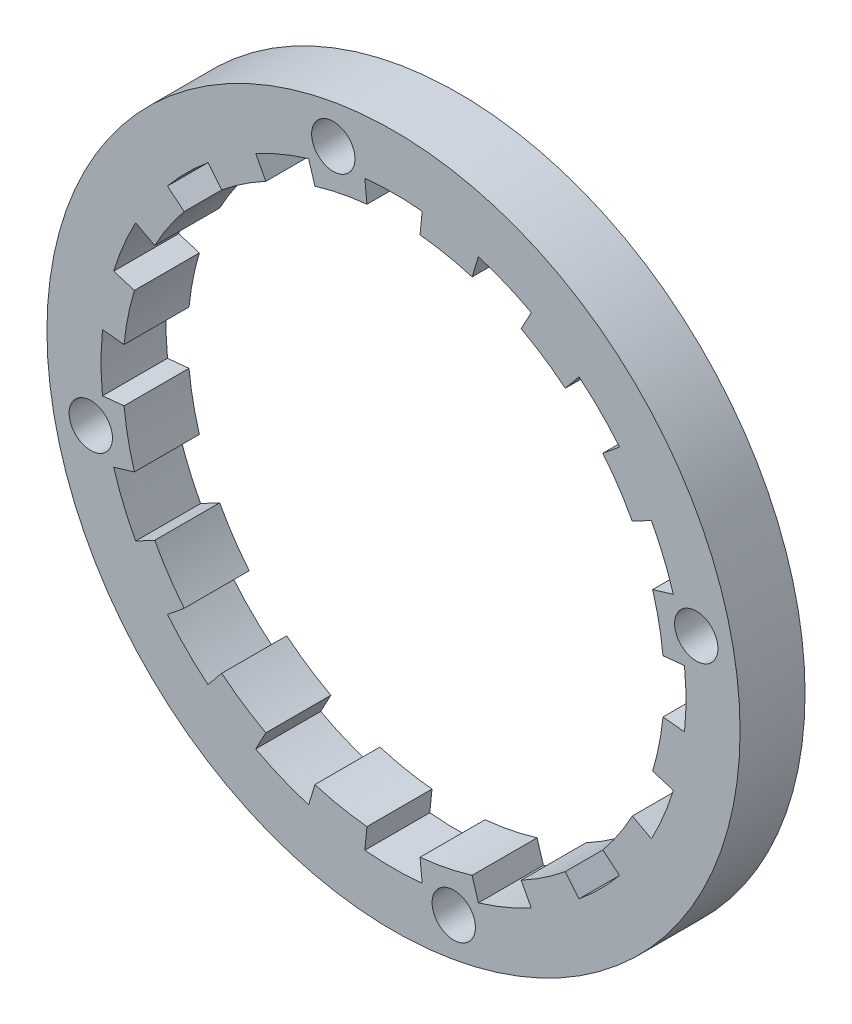
SolidWorks part; units mm, degrees
ref_plane "Plano frontal" through (0, 0, 0) normal (0, 0, 1) x (1, 0, 0)
ref_plane "Plano superior" through (0, 0, 0) normal (0, 1, 0) x (1, 0, 0)
ref_plane "Plano direito" through (0, 0, 0) normal (1, 0, 0) x (0, 0, -1)
sketch "Esboço1" plane through (0, 0, 0) normal (0, 0, 1) x (1, 0, 0)
  line L0 (0, 32) -> (0, -32) construction
  line L1 (-32, 0) -> (32, 0) construction
  line L2 (-22.6274, 22.6274) -> (22.6274, -22.6274) construction
  line L3 (22.6274, 22.6274) -> (-22.6274, -22.6274) construction
  line L4 (-29.5641, 12.2459) -> (29.5641, -12.2459) construction
  line L5 (-29.5641, -12.2459) -> (29.5641, 12.2459) construction
  line L6 (-12.2459, -29.5641) -> (12.2459, 29.5641) construction
  line L7 (12.2459, -29.5641) -> (-12.2459, 29.5641) construction
  line L40 (-5.2674, 26.4812) -> (5.2674, -26.4812) construction
  line L41 (5.2674, 26.4812) -> (-5.2674, -26.4812) construction
  line L42 (15.0004, 22.4497) -> (-15.0004, -22.4497) construction
  line L43 (22.4497, 15.0004) -> (-22.4497, -15.0004) construction
  line L44 (26.4812, 5.2674) -> (-26.4812, -5.2674) construction
  line L45 (26.4812, -5.2674) -> (-26.4812, 5.2674) construction
  line L46 (22.4497, -15.0004) -> (-22.4497, 15.0004) construction
  line L47 (15.0004, -22.4497) -> (-15.0004, 22.4497) construction
  line L48 (5.2674, -26.4812) -> (-5.2674, 26.4812) construction
  line L49 (-5.2674, -26.4812) -> (5.2674, 26.4812) construction
  line L50 (-15.0004, -22.4497) -> (15.0004, 22.4497) construction
  line L51 (-22.4497, -15.0004) -> (22.4497, 15.0004) construction
  line L52 (-26.4812, -5.2674) -> (26.4812, 5.2674) construction
  line L53 (-26.4812, 5.2674) -> (26.4812, -5.2674) construction
  line L54 (-22.4497, 15.0004) -> (22.4497, -15.0004) construction
  line L55 (-15.0004, 22.4497) -> (15.0004, -22.4497) construction
  line L56 (-7.2571, 23.9235) -> (7.2571, -23.9235) construction
  line L57 (-2.4504, 24.8796) -> (2.1564, -21.8941) construction
  line L58 (2.4504, 24.8796) -> (-2.4504, -24.8796) construction
  line L59 (7.2571, 23.9235) -> (-5.5154, -18.1819) construction
  line L60 (11.7849, 22.048) -> (-8.9565, -16.7565) construction
  line L61 (15.8598, 19.3253) -> (-12.0535, -14.6872) construction
  line L62 (14.6872, 12.0535) -> (-19.3253, -15.8598) construction
  line L63 (19.4023, 10.3707) -> (-19.4023, -10.3707) construction
  line L64 (21.0527, 6.3863) -> (-21.0527, -6.3863) construction
  line L65 (21.8941, 2.1564) -> (-21.8941, -2.1564) construction
  line L66 (21.8941, -2.1564) -> (-21.8941, 2.1564) construction
  line L67 (21.0527, -6.3863) -> (-21.0527, 6.3863) construction
  line L68 (19.4023, -10.3707) -> (-19.4023, 10.3707) construction
  line L69 (17.0062, -13.9567) -> (-17.0062, 13.9567) construction
  line L70 (13.9567, -17.0062) -> (-13.9567, 17.0062) construction
  line L71 (10.3707, -19.4023) -> (-10.3707, 19.4023) construction
  line L72 (6.3863, -21.0527) -> (-6.3863, 21.0527) construction
  line L73 (2.4504, -24.8796) -> (-2.4504, 24.8796) construction
  line L74 (-1.8623, -18.9085) -> (2.4504, 24.8796) construction
  line L75 (-6.3863, -21.0527) -> (6.3863, 21.0527) construction
  line L76 (-10.3707, -19.4023) -> (10.3707, 19.4023) construction
  line L77 (-13.9567, -17.0062) -> (13.9567, 17.0062) construction
  line L78 (-17.0062, -13.9567) -> (17.0062, 13.9567) construction
  line L79 (-19.4023, -10.3707) -> (19.4023, 10.3707) construction
  line L80 (-21.0527, -6.3863) -> (21.0527, 6.3863) construction
  line L81 (-21.8941, -2.1564) -> (21.8941, 2.1564) construction
  line L82 (-21.8941, 2.1564) -> (21.8941, -2.1564) construction
  line L83 (-21.0527, 6.3863) -> (21.0527, -6.3863) construction
  line L84 (-19.4023, 10.3707) -> (19.4023, -10.3707) construction
  line L85 (-19.3253, 15.8598) -> (14.6872, -12.0535) construction
  line L86 (-12.0535, 14.6872) -> (15.8598, -19.3253) construction
  line L87 (-8.9565, 16.7565) -> (11.7849, -22.048) construction
  line L88 (0, 0) -> (-2.6465, 26.87) construction
  line L89 (0, 0) -> (2.6465, 26.87) construction
  line L90 (-2.6465, 26.87) -> (-2.4504, 24.8796)
  line L91 (2.6465, 26.87) -> (2.4504, 24.8796)
  line L92 (7.8377, 25.8374) -> (7.2571, 23.9235)
  line L93 (12.7277, 23.8119) -> (11.7849, 22.048)
  line L94 (17.1286, 20.8713) -> (15.8598, 19.3253)
  line L95 (20.8713, 17.1286) -> (19.3253, 15.8598)
  line L96 (23.8119, 12.7277) -> (22.048, 11.7849)
  line L97 (25.8374, 7.8377) -> (23.9235, 7.2571)
  line L98 (26.87, 2.6465) -> (24.8796, 2.4504)
  line L99 (26.87, -2.6465) -> (24.8796, -2.4504)
  line L100 (25.8374, -7.8377) -> (23.9235, -7.2571)
  line L101 (23.8119, -12.7277) -> (22.048, -11.7849)
  line L102 (20.8713, -17.1286) -> (19.3253, -15.8598)
  line L103 (17.1286, -20.8713) -> (15.8598, -19.3253)
  line L104 (12.7277, -23.8119) -> (11.7849, -22.048)
  line L105 (7.8377, -25.8374) -> (7.2571, -23.9235)
  line L106 (2.6465, -26.87) -> (2.4504, -24.8796)
  line L107 (-2.6465, -26.87) -> (-2.4504, -24.8796)
  line L108 (-7.8377, -25.8374) -> (-7.2571, -23.9235)
  line L109 (-12.7277, -23.8119) -> (-11.7849, -22.048)
  line L110 (-17.1286, -20.8713) -> (-15.8598, -19.3253)
  line L111 (-20.8713, -17.1286) -> (-19.3253, -15.8598)
  line L112 (-23.8119, -12.7277) -> (-22.048, -11.7849)
  line L113 (-25.8374, -7.8377) -> (-23.9235, -7.2571)
  line L114 (-26.87, -2.6465) -> (-24.8796, -2.4504)
  line L115 (-26.87, 2.6465) -> (-24.8796, 2.4504)
  line L116 (-25.8374, 7.8377) -> (-23.9235, 7.2571)
  line L117 (-23.8119, 12.7277) -> (-22.048, 11.7849)
  line L118 (-20.8713, 17.1286) -> (-19.3253, 15.8598)
  line L119 (-17.1286, 20.8713) -> (-15.8598, 19.3253)
  line L120 (-12.7277, 23.8119) -> (-11.7849, 22.048)
  line L121 (-7.8377, 25.8374) -> (-7.2571, 23.9235)
  circle A0 centre (0, 0) radius 32
  circle A1 centre (0, 0) radius 27 construction
  arc A2 (-19.3253, 15.8598) -> (-22.048, 11.7849) centre (0, 0) ccw
  arc A3 (0, 27) -> (-2.6465, 26.87) centre (0, 0) ccw
  arc A4 (0, 27) -> (2.6465, 26.87) centre (0, 0) cw
  arc A5 (10.3325, 24.9447) -> (7.8377, 25.8374) centre (0, 0) ccw
  arc A6 (10.3325, 24.9447) -> (12.7277, 23.8119) centre (0, 0) cw
  arc A7 (19.0919, 19.0919) -> (17.1286, 20.8713) centre (0, 0) ccw
  arc A8 (19.0919, 19.0919) -> (20.8713, 17.1286) centre (0, 0) cw
  arc A9 (24.9447, 10.3325) -> (23.8119, 12.7277) centre (0, 0) ccw
  arc A10 (24.9447, 10.3325) -> (25.8374, 7.8377) centre (0, 0) cw
  arc A11 (27, 0) -> (26.87, 2.6465) centre (0, 0) ccw
  arc A12 (27, 0) -> (26.87, -2.6465) centre (0, 0) cw
  arc A13 (24.9447, -10.3325) -> (25.8374, -7.8377) centre (0, 0) ccw
  arc A14 (24.9447, -10.3325) -> (23.8119, -12.7277) centre (0, 0) cw
  arc A15 (19.0919, -19.0919) -> (20.8713, -17.1286) centre (0, 0) ccw
  arc A16 (19.0919, -19.0919) -> (17.1286, -20.8713) centre (0, 0) cw
  arc A17 (10.3325, -24.9447) -> (12.7277, -23.8119) centre (0, 0) ccw
  arc A18 (10.3325, -24.9447) -> (7.8377, -25.8374) centre (0, 0) cw
  arc A19 (0, -27) -> (2.6465, -26.87) centre (0, 0) ccw
  arc A20 (0, -27) -> (-2.6465, -26.87) centre (0, 0) cw
  arc A21 (-10.3325, -24.9447) -> (-7.8377, -25.8374) centre (0, 0) ccw
  arc A22 (-10.3325, -24.9447) -> (-12.7277, -23.8119) centre (0, 0) cw
  arc A23 (-19.0919, -19.0919) -> (-17.1286, -20.8713) centre (0, 0) ccw
  arc A24 (-19.0919, -19.0919) -> (-20.8713, -17.1286) centre (0, 0) cw
  arc A25 (-24.9447, -10.3325) -> (-23.8119, -12.7277) centre (0, 0) ccw
  arc A26 (-24.9447, -10.3325) -> (-25.8374, -7.8377) centre (0, 0) cw
  arc A27 (-27, 0) -> (-26.87, -2.6465) centre (0, 0) ccw
  arc A28 (-27, 0) -> (-26.87, 2.6465) centre (0, 0) cw
  arc A29 (-24.9447, 10.3325) -> (-25.8374, 7.8377) centre (0, 0) ccw
  arc A30 (-24.9447, 10.3325) -> (-23.8119, 12.7277) centre (0, 0) cw
  arc A31 (-19.0919, 19.0919) -> (-20.8713, 17.1286) centre (0, 0) ccw
  arc A32 (-19.0919, 19.0919) -> (-17.1286, 20.8713) centre (0, 0) cw
  arc A33 (-10.3325, 24.9447) -> (-12.7277, 23.8119) centre (0, 0) ccw
  arc A34 (-10.3325, 24.9447) -> (-7.8377, 25.8374) centre (0, 0) cw
  arc A35 (-23.9235, 7.2571) -> (-24.8796, 2.4504) centre (0, 0) ccw
  arc A36 (-24.8796, -2.4504) -> (-23.9235, -7.2571) centre (0, 0) ccw
  arc A37 (-22.048, -11.7849) -> (-19.3253, -15.8598) centre (0, 0) ccw
  arc A38 (-11.7849, 22.048) -> (-15.8598, 19.3253) centre (0, 0) ccw
  arc A39 (-2.4504, 24.8796) -> (-7.2571, 23.9235) centre (0, 0) ccw
  arc A40 (7.2571, 23.9235) -> (2.4504, 24.8796) centre (0, 0) ccw
  arc A41 (15.8598, 19.3253) -> (11.7849, 22.048) centre (0, 0) ccw
  arc A42 (22.048, 11.7849) -> (19.3253, 15.8598) centre (0, 0) ccw
  arc A43 (24.8796, 2.4504) -> (23.9235, 7.2571) centre (0, 0) ccw
  arc A44 (23.9235, -7.2571) -> (24.8796, -2.4504) centre (0, 0) ccw
  arc A45 (19.3253, -15.8598) -> (22.048, -11.7849) centre (0, 0) ccw
  arc A46 (11.7849, -22.048) -> (15.8598, -19.3253) centre (0, 0) ccw
  arc A47 (2.4504, -24.8796) -> (7.2571, -23.9235) centre (0, 0) ccw
  arc A48 (-7.2571, -23.9235) -> (-2.4504, -24.8796) centre (0, 0) ccw
  arc A49 (-15.8598, -19.3253) -> (-11.7849, -22.048) centre (0, 0) ccw
  point P55 (0, 0)
  point P72 (0, 0)
  point P121 (0, 0)
  point P202 (0, 0)
  dimension "D1" = 64
  dimension "D2" = 54
  dimension "D9" = 2
  dimension "D3" = 45
  dimension "D4" = 45
  dimension "D5" = 22.5
  dimension "D6" = 22.5
  dimension "D7" = 22.5
  dimension "D8" = 22.5
  dimension "D10" = 11.25
  dimension "D12" = 5.625
  dimension "D14" = 16
extrude "Ressalto-extrusão4" add sketch "Esboço1" along normal blind 6
sketch "Esboço2" plane through (0, 0, 6) normal (0, 0, 1) x (1, 0, 0)
  line L0 (-6.2429, 31.3851) -> (-5.5601, 27.9524)
  line L1 (-6.2429, 31.3851) -> (6.2429, -31.3851) construction
  line L2 (-5.5601, 27.9524) -> (-4.8773, 24.5196)
  line L3 (6.2429, -31.3851) -> (5.5601, -27.9524)
  line L4 (5.5601, -27.9524) -> (4.8773, -24.5196)
  circle A1 centre (0, 0) radius 32 construction
  circle A2 centre (-5.5601, 27.9524) radius 2
  arc A3 (-2.4504, 24.8796) -> (-7.2571, 23.9235) centre (0, 0) ccw construction
  circle A4 centre (5.5601, -27.9524) radius 2
  arc A5 (2.4504, -24.8796) -> (7.2571, -23.9235) centre (0, 0) ccw construction
  circle A6 centre (27.9524, 5.5601) radius 2
  circle A7 centre (-27.9524, -5.5601) radius 2
  circle A8 centre (5.5601, -27.9524) radius 2
  circle A9 centre (-5.5601, 27.9524) radius 2
  circle A10 centre (-27.9524, -5.5601) radius 2
  circle A11 centre (27.9524, 5.5601) radius 2
  point P31 (0, 0)
  point P32 (-12.3998, 8.1612)
  dimension "D1" = 4
  dimension "D2" = 4
  dimension "D3" = 4
extrude "Corte-extrusão1" cut sketch "Esboço2" against normal blind 6 contours A2 | A7 | A6 | A4
